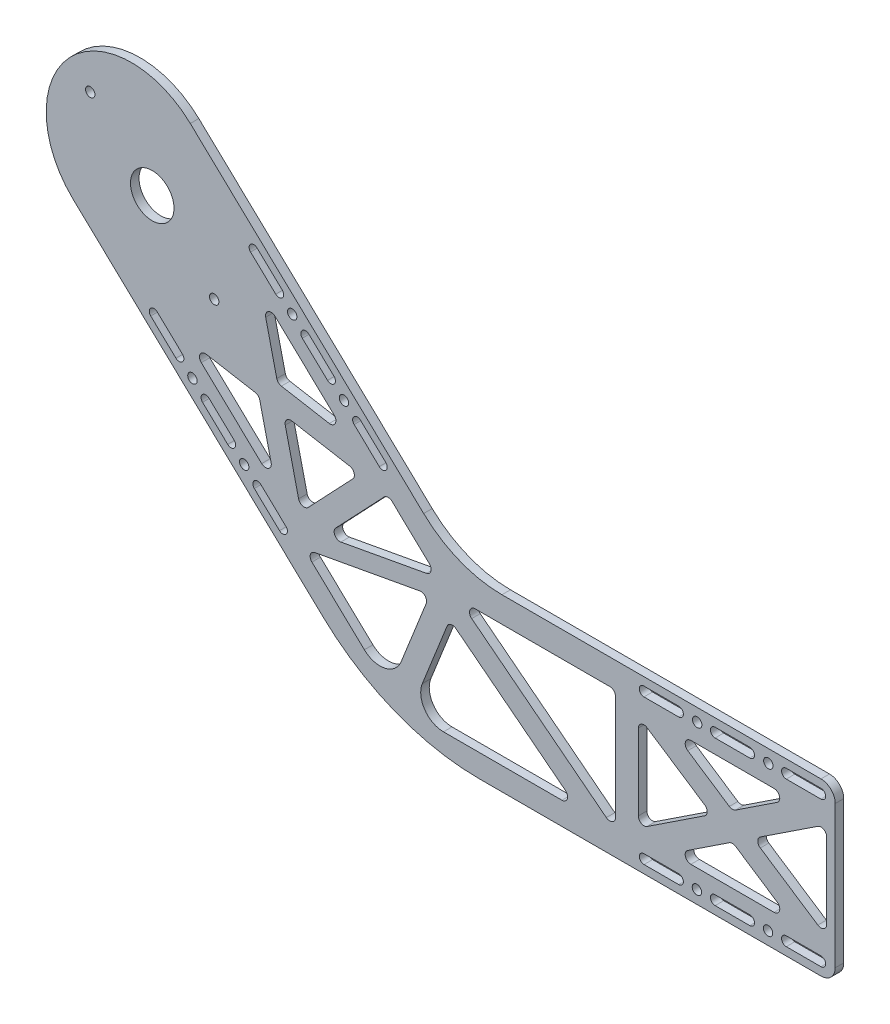
SolidWorks part; units mm, degrees
material "Thornel Mat VMA"
ref_plane "前视基准面" through (0, 0, 0) normal (0, 0, 1) x (1, 0, 0)
ref_plane "上视基准面" through (0, 0, 0) normal (0, 1, 0) x (1, 0, 0)
ref_plane "右视基准面" through (0, 0, 0) normal (1, 0, 0) x (0, 0, -1)
sketch "草图1" plane through (0, 0, 0) normal (0, 0, 1) x (1, 0, 0)
  line L0 (0, 0) -> (95, -90) construction
  line L1 (95, -90) -> (345, -90) construction
  line L2 (-20.6323, -21.7786) -> (83.0458, -120)
  line L3 (83.0458, -120) -> (345, -120)
  line L4 (20.6323, 21.7786) -> (106.9542, -60)
  line L5 (106.9542, -60) -> (345, -60)
  line L6 (345, -60) -> (345, -120)
  circle A1 centre (0, 0) radius 7.65
  circle A2 centre (0, 0) radius 30
  dimension "D6" = 15.3
  dimension "D1" = 250
  dimension "D2" = 345
  dimension "D3" = 90
  dimension "D4" = 30
  dimension "D5" = 30
extrude "凸台-拉伸1" add sketch "草图1" along normal blind 3
sketch "草图2" plane through (0, 0, 3) normal (0, 0, 1) x (1, 0, 0)
  line L0 (345, -90) -> (114.5407, -90) construction
  line L1 (345, -60) -> (345, -120) construction
  circle A0 centre (305, -90) radius 5
  circle A1 centre (278, -90) radius 5
  circle A2 centre (332, -90) radius 5
  dimension "D1" = 305
  dimension "D2" = 10
  dimension "D3" = 27
  dimension "D4" = 27
extrude "切除-拉伸1" cut sketch "草图2" against normal through all
sketch "草图3" plane through (0, 0, 3) normal (0, 0, 1) x (1, 0, 0)
  line L0 (345, -64.5) -> (105.161, -64.5) construction
  line L1 (345, -60) -> (345, -120) construction
  line L2 (345, -115.5) -> (84.839, -115.5) construction
  line L3 (106.9542, -60) -> (345, -60) construction
  line L4 (83.0458, -120) -> (345, -120) construction
  line L5 (222.8, -115.5) -> (235, -115.5) construction
  line L6 (222.8, -113.85) -> (235, -113.85)
  line L7 (222.8, -117.15) -> (235, -117.15)
  line L8 (345, -90) -> (113.6838, -90) construction
  line L9 (222.8, -64.5) -> (235, -64.5) construction
  line L10 (222.8, -66.15) -> (235, -66.15)
  line L11 (222.8, -62.85) -> (235, -62.85)
  line L12 (35.6863, 1.3182) -> (44.5429, -7.0723) construction
  line L13 (36.8211, 2.516) -> (45.6777, -5.8745)
  line L14 (34.5515, 0.1204) -> (43.4081, -8.2701)
  line L15 (0.6594, -35.6546) -> (104.3375, -133.876) construction
  line L16 (18.8082, -52.8482) -> (27.6648, -61.2387) construction
  line L17 (19.943, -51.6504) -> (28.7996, -60.0408)
  line L18 (-17.5375, -18.5118) -> (86.1407, -116.7332)
  line L19 (-17.5375, -18.5118) -> (86.1407, -116.7332) construction
  line L20 (197.8, -115.5) -> (210, -115.5) construction
  line L21 (17.5375, 18.5118) -> (103.8593, -63.2668)
  line L22 (17.5375, 18.5118) -> (103.8593, -63.2668) construction
  line L23 (197.8, -113.85) -> (210, -113.85)
  line L24 (197.8, -117.15) -> (210, -117.15)
  line L25 (197.8, -64.5) -> (210, -64.5) construction
  line L26 (197.8, -66.15) -> (210, -66.15)
  line L27 (197.8, -62.85) -> (210, -62.85)
  line L28 (172.8, -115.5) -> (185, -115.5) construction
  line L29 (172.8, -113.85) -> (185, -113.85)
  line L30 (172.8, -117.15) -> (185, -117.15)
  line L31 (172.8, -64.5) -> (185, -64.5) construction
  line L32 (172.8, -66.15) -> (185, -66.15)
  line L33 (172.8, -62.85) -> (185, -62.85)
  line L34 (17.6734, -54.046) -> (26.53, -62.4365)
  line L37 (0.6113, -35.7054) -> (9.468, -44.0959) construction
  line L38 (1.7461, -34.5076) -> (10.6027, -42.8981)
  line L39 (-0.5235, -36.9032) -> (8.3332, -45.2937)
  line L40 (53.8832, -15.8246) -> (62.7398, -24.2151) construction
  line L41 (55.0179, -14.6268) -> (63.8746, -23.0173)
  line L42 (52.7484, -17.0224) -> (61.605, -25.4129)
  line L43 (18.8562, -52.7973) -> (122.5344, -151.0187) construction
  line L44 (37.005, -69.9909) -> (45.8617, -78.3814) construction
  line L45 (38.1398, -68.7931) -> (46.9964, -77.1836)
  line L46 (35.8703, -71.1888) -> (44.7269, -79.5792)
  line L47 (72.08, -32.9674) -> (80.9366, -41.3578) construction
  line L48 (73.2148, -31.7695) -> (82.0714, -40.16)
  line L49 (70.9452, -34.1652) -> (79.8019, -42.5557)
  arc A0 (222.8, -113.85) -> (222.8, -117.15) centre (222.8, -115.5) ccw
  arc A1 (235, -117.15) -> (235, -113.85) centre (235, -115.5) ccw
  arc A2 (222.8, -66.15) -> (222.8, -62.85) centre (222.8, -64.5) cw
  arc A3 (235, -62.85) -> (235, -66.15) centre (235, -64.5) cw
  circle A4 centre (216.4, -115.5) radius 1.65
  circle A5 centre (216.5, -64.5) radius 1.65
  circle A6 centre (191.5, -64.5) radius 1.65
  circle A7 centre (191.4, -115.5) radius 1.65
  arc A8 (197.8, -113.85) -> (197.8, -117.15) centre (197.8, -115.5) ccw
  arc A9 (210, -117.15) -> (210, -113.85) centre (210, -115.5) ccw
  arc A10 (197.8, -66.15) -> (197.8, -62.85) centre (197.8, -64.5) cw
  arc A11 (210, -62.85) -> (210, -66.15) centre (210, -64.5) cw
  arc A14 (172.8, -113.85) -> (172.8, -117.15) centre (172.8, -115.5) ccw
  arc A15 (185, -117.15) -> (185, -113.85) centre (185, -115.5) ccw
  arc A16 (172.8, -66.15) -> (172.8, -62.85) centre (172.8, -64.5) cw
  arc A17 (185, -62.85) -> (185, -66.15) centre (185, -64.5) cw
  circle A18 centre (166.4, -115.5) radius 1.65 [skipped]
  circle A19 centre (166.5, -64.5) radius 1.65 [skipped]
  arc A23 (1.7461, -34.5076) -> (-0.5235, -36.9032) centre (0.6113, -35.7054) ccw
  arc A24 (8.3332, -45.2937) -> (10.6027, -42.8981) centre (9.468, -44.0959) ccw
  circle A25 centre (14.114, -48.4975) radius 1.65
  arc A26 (36.8211, 2.516) -> (34.5515, 0.1204) centre (35.6863, 1.3182) ccw
  arc A27 (43.4081, -8.2701) -> (45.6777, -5.8745) centre (44.5429, -7.0723) ccw
  circle A28 centre (49.189, -11.4739) radius 1.65
  circle A29 centre (67.3859, -28.6166) radius 1.65
  circle A30 centre (32.3109, -65.6402) radius 1.65
  arc A31 (19.943, -51.6504) -> (17.6734, -54.046) centre (18.8082, -52.8482) ccw
  arc A32 (26.53, -62.4365) -> (28.7996, -60.0408) centre (27.6648, -61.2387) ccw
  arc A33 (55.0179, -14.6268) -> (52.7484, -17.0224) centre (53.8832, -15.8246) ccw
  arc A34 (61.605, -25.4129) -> (63.8746, -23.0173) centre (62.7398, -24.2151) ccw
  arc A37 (38.1398, -68.7931) -> (35.8703, -71.1888) centre (37.005, -69.9909) ccw
  arc A38 (44.7269, -79.5792) -> (46.9964, -77.1836) centre (45.8617, -78.3814) ccw
  arc A39 (73.2148, -31.7695) -> (70.9452, -34.1652) centre (72.08, -32.9674) ccw
  arc A40 (79.8019, -42.5557) -> (82.0714, -40.16) centre (80.9366, -41.3578) ccw
  circle A41 centre (85.5827, -45.7594) radius 1.65 [skipped]
  circle A42 centre (50.5078, -82.783) radius 1.65 [skipped]
  point P12 (228.9, -115.5)
  point P21 (228.9, -64.5)
  point P38 (203.9, -115.5)
  point P45 (203.9, -64.5)
  point P56 (178.9, -115.5)
  point P63 (178.9, -64.5)
  point P68 (40.1146, -2.8771)
  point P81 (5.0396, -39.9007)
  point P93 (58.3115, -20.0198)
  point P102 (23.2365, -57.0434)
  point P113 (76.5083, -37.1626)
  point P122 (41.4334, -74.1862)
  dimension "D8" = 6.4
  dimension "D9" = 3.3
  dimension "D10" = 3.3
  dimension "D11" = 6.3
  dimension "D14" = 3.3
  dimension "D16" = 3.3
  dimension "D18" = 6.4
  dimension "D22" = 3.3
  dimension "D23" = 6.4
  dimension "D1" = 4.5
  dimension "D2" = 4.5
  dimension "D3" = 12.2
  dimension "D4" = 110
  dimension "D5" = 3.3
  dimension "D13" = 12.8
  dimension "D15" = 12.2
  dimension "D17" = 25
  dimension "D19" = 25
  dimension "D20" = 12.2
  dimension "D21" = 3.3
  dimension "D25" = 12.8001
  dimension "D6" = 4.5
  dimension "D7" = 4.5
  dimension "D12" = 3
  dimension "D24" = 3
fillet "圆角1" radius 20 2 edges at (345, -120, 1.5) (345, -60, 1.5)
extrude "切除-拉伸2" cut sketch "草图3" against normal through all
fillet "圆角2" radius 40 1 edges at (106.9542, -60, 1.5)
fillet "圆角3" radius 80 1 edges at (83.0458, -120, 1.5)
sketch "草图4" plane through (0, 0, 3) normal (0, 0, 1) x (1, 0, 0)
  line L0 (122.8931, -60) -> (325, -60) construction
  line L1 (240, -60) -> (345, -60)
  line L2 (240, -60) -> (240, -120)
  line L3 (240, -120) -> (345, -120)
  line L4 (345, -60) -> (345, -120)
  line L5 (345, -80) -> (345, -100) construction
  line L6 (114.9236, -120) -> (325, -120) construction
  arc A1 (235, -66.15) -> (235, -62.85) centre (235, -64.5) ccw construction
  dimension "D1" = 5
extrude "切除-拉伸3" cut sketch "草图4" against normal through all
fillet "圆角4" radius 5 2 edges at (240, -120, 1.5) (240, -60, 1.5)
sketch "草图5" plane through (0, 0, 3) normal (0, 0, 1) x (1, 0, 0)
  line L0 (122.8931, -60) -> (235, -60) construction
  line L1 (167.8, -60) -> (240, -60) construction
  line L2 (167.8, -60) -> (167.8, -120) construction
  line L3 (167.8, -120) -> (240, -120) construction
  line L4 (240, -60) -> (240, -120) construction
  line L5 (240, -65) -> (240, -115) construction
  line L6 (114.9236, -120) -> (235, -120) construction
  line L7 (170.8, -107.0739) -> (170.8, -72.9261)
  line L8 (167.8, -66.15) -> (240, -113.85) construction
  line L9 (167.8, -113.85) -> (240, -66.15) construction
  line L10 (107.6738, -69) -> (162.8, -69)
  line L11 (162.8, -69) -> (162.8, -112)
  line L12 (222.8, -66.15) -> (235, -66.15) construction
  line L13 (185, -113.85) -> (172.8, -113.85) construction
  line L14 (170.8, -72.9261) -> (196.6435, -90)
  line L15 (196.6435, -90) -> (170.8, -107.0739)
  line L16 (182.6247, -71.15) -> (203.9, -85.2059)
  line L17 (203.9, -85.2059) -> (225.1753, -71.15)
  line L18 (225.1753, -71.15) -> (182.6247, -71.15)
  line L19 (211.1565, -90) -> (237, -72.9261)
  line L20 (237, -72.9261) -> (237, -107.0739)
  line L21 (237, -107.0739) -> (211.1565, -90)
  line L22 (182.6247, -108.85) -> (203.9, -94.7941)
  line L23 (203.9, -94.7941) -> (225.1753, -108.85)
  line L24 (225.1753, -108.85) -> (182.6247, -108.85)
  line L25 (210, -113.85) -> (197.8, -113.85) construction
  line L26 (197.8, -66.15) -> (210, -66.15) construction
  line L35 (35.1514, 8.0237) -> (-6.1133, -35.5335) construction
  line L36 (35.9178, -1.174) -> (30.9218, 3.5591) construction
  line L37 (162.8, -112) -> (107.6738, -69)
  line L38 (104.5895, -76.7402) -> (149.7928, -112)
  line L43 (149.7928, -112) -> (90.5395, -112)
  line L44 (90.5395, -112) -> (104.5895, -76.7402)
  line L45 (83.1078, -109.0387) -> (97.6197, -72.6197)
  line L46 (97.6197, -72.6197) -> (53.2542, -80.7564)
  line L47 (53.2542, -80.7564) -> (83.1078, -109.0387)
  line L48 (60.2485, -73.3735) -> (82.8272, -49.5404)
  line L49 (82.8272, -49.5404) -> (100.2421, -66.0387)
  line L50 (100.2421, -66.0387) -> (60.2485, -73.3735)
  line L51 (20.6323, 21.7786) -> (95.3833, -49.0381) construction
  line L52 (-20.6323, -21.7786) -> (59.9041, -98.0762) construction
  line L53 (122.8931, -20) -> (85.3103, -114.3172) construction
  line L54 (87.565, -41.6313) -> (46.3004, -85.1885) construction
  line L55 (34.5515, 0.1204) -> (43.4081, -8.2701) construction
  line L56 (77.0055, -39.9065) -> (83.4316, -45.9944) construction
  line L57 (70.9452, -34.1652) -> (79.8019, -42.5557) construction
  line L58 (44.3671, -74.6927) -> (50.6262, -80.6223) construction
  line L59 (46.9964, -77.1836) -> (38.1398, -68.7931) construction
  line L60 (4.1769, -36.8105) -> (-1.8837, -31.0689) construction
  line L61 (10.6027, -42.8981) -> (1.7461, -34.5076) construction
  line L62 (-1.8837, -31.0689) -> (83.4316, -45.9944) construction
  line L63 (83.4316, -45.9944) -> (30.9218, 3.5591) construction
  line L64 (30.9218, 3.5591) -> (50.6262, -80.6223) construction
  line L68 (12.415, -37.6311) -> (37.4815, -42.0164)
  line L69 (37.4815, -42.0164) -> (43.305, -66.8953)
  line L70 (43.305, -66.8953) -> (12.415, -37.6311)
  line L71 (38.3341, -10.5573) -> (44.0664, -35.0469)
  line L72 (44.0664, -35.0469) -> (68.7407, -39.3635)
  line L73 (68.7407, -39.3635) -> (38.3341, -10.5573)
  line L74 (46.0486, -43.5151) -> (73.0416, -48.2375)
  line L75 (73.0416, -48.2375) -> (52.2829, -70.1494)
  line L76 (52.2829, -70.1494) -> (46.0486, -43.5151)
  line L77 (28.7996, -60.0408) -> (19.943, -51.6504) construction
  arc A0 (79.8019, -42.5557) -> (82.0714, -40.16) centre (80.9366, -41.3578) ccw construction
  arc A1 (172.8, -62.85) -> (172.8, -66.15) centre (172.8, -64.5) ccw construction
  arc A2 (36.8211, 2.516) -> (34.5515, 0.1204) centre (35.6863, 1.3182) ccw construction
  arc A3 (95.3833, -49.0381) -> (122.8931, -60) centre (122.8931, -20) ccw construction
  arc A4 (95.3833, -49.0381) -> (122.8931, -60) centre (122.8931, -20) ccw construction
  arc A6 (59.9041, -98.0762) -> (114.9236, -120) centre (114.9236, -40) ccw construction
  dimension "D1" = 5
  dimension "D17" = 5
  dimension "D18" = 5
  dimension "D2" = 5
  dimension "D3" = 8
  dimension "D4" = 8
  dimension "D5" = 6
  dimension "D6" = 5
  dimension "D7" = 6
  dimension "D8" = 9
  dimension "D9" = 8
  dimension "D10" = 7
  dimension "D11" = 9
  dimension "D12" = 5
  dimension "D13" = 8
  dimension "D14" = 6
  dimension "D15" = 8
  dimension "D16" = 8
  dimension "D21" = 11.3
  dimension "D22" = 5
  dimension "D23" = 6
extrude "切除-拉伸4" cut sketch "草图5" against normal through all
fillet "圆角5" radius 2 31 edges at (203.9, -85.2059, 1.5) (225.1753, -71.15, 1.5) (237, -72.9261, 1.5) (237, -107.0739, 1.5) (225.1753, -108.85, 1.5) (203.9, -94.7941, 1.5) (196.6435, -90, 1.5) (182.6247, -108.85, 1.5) (211.1565, -90, 1.5) (182.6247, -71.15, 1.5) (170.8, -107.0739, 1.5) (170.8, -72.9261, 1.5) (162.8, -69, 1.5) (107.6738, -69, 1.5) (162.8, -112, 1.5) (149.7928, -112, 1.5) (104.5895, -76.7402, 1.5) (82.8272, -49.5404, 1.5) (60.2485, -73.3735, 1.5) (100.2421, -66.0387, 1.5) (97.6197, -72.6197, 1.5) (53.2542, -80.7564, 1.5) (73.0416, -48.2375, 1.5) (68.7407, -39.3635, 1.5) (44.0664, -35.0469, 1.5) (38.3341, -10.5573, 1.5) (46.0486, -43.5151, 1.5) (52.2829, -70.1494, 1.5) (43.305, -66.8953, 1.5) (37.4815, -42.0164, 1.5) (12.415, -37.6311, 1.5)
fillet "圆角6" radius 8 2 edges at (90.5395, -112, 1.5) (83.1078, -109.0387, 1.5)
sketch "草图6" plane through (0, 0, 3) normal (0, 0, 1) x (1, 0, 0)
  line L0 (20.6323, 21.7786) -> (13.3728, 28.656)
  line L1 (-27.8919, -14.9011) -> (-20.6323, -21.7786)
  line L2 (-20.6323, -21.7786) -> (59.9041, -98.0762) construction
  line L3 (20.6323, 21.7786) -> (95.3833, -49.0381) construction
  arc A0 (13.3728, 28.656) -> (-27.8919, -14.9011) centre (-7.2595, 6.8774) ccw
  arc A1 (-20.6323, -21.7786) -> (20.6323, 21.7786) centre (0, 0) cw
  dimension "D1" = 10
extrude "凸台-拉伸2" add sketch "草图6" against normal blind 3 contours L1 A1 L0 A0
sketch "草图7" plane through (0, 0, 3) normal (0, 0, 1) x (1, 0, 0)
  line L0 (-29.0381, 27.5098) -> (0, 0) construction
  line L1 (13.3728, 28.656) -> (95.3833, -49.0381) construction
  arc A0 (13.3728, 28.656) -> (-27.8919, -14.9011) centre (-7.2595, 6.8774) ccw construction
  circle A1 centre (-21.7786, 20.6323) radius 1.65
  circle A2 centre (21.7786, -20.6323) radius 1.65
  point P12 (0, 0)
  dimension "D1" = 3.3
  dimension "D2" = 30
  dimension "D4" = 3.3
  dimension "D3" = 30
extrude "切除-拉伸5" cut sketch "草图7" against normal blind 3
